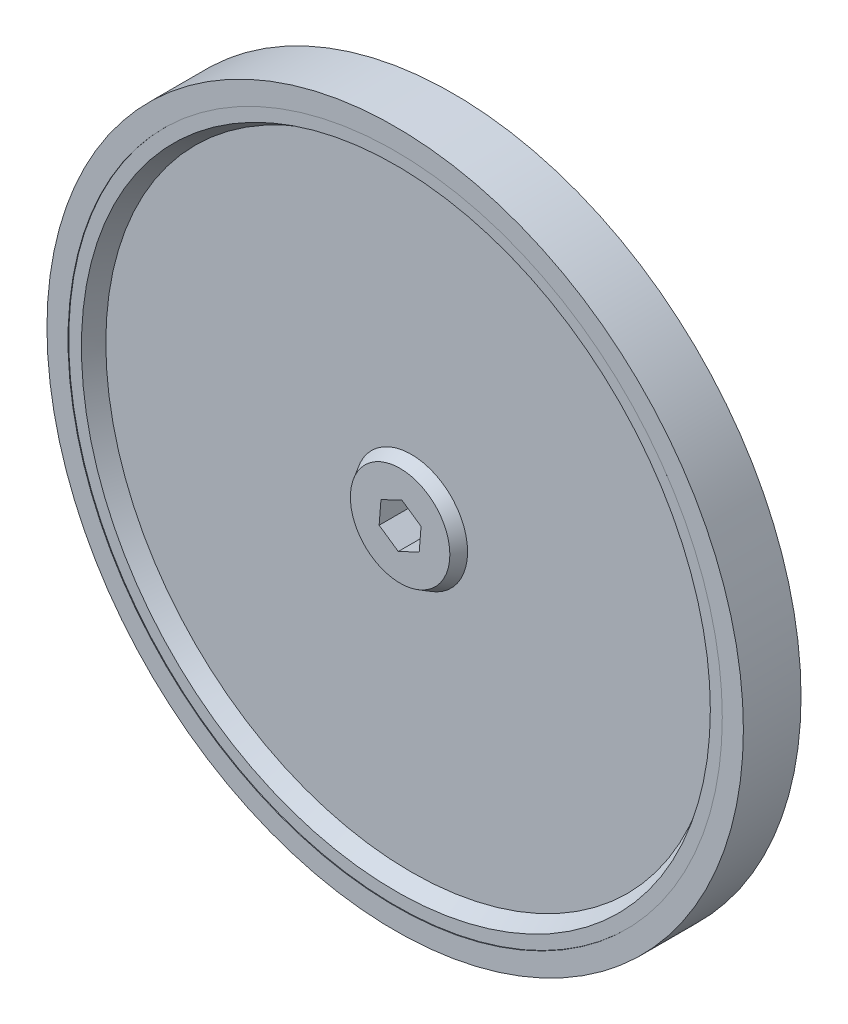
SolidWorks part; units mm, degrees
ref_plane "Front Plane" through (0, 0, 0) normal (0, 0, 1) x (1, 0, 0)
ref_plane "Top Plane" through (0, 0, 0) normal (0, 1, 0) x (1, 0, 0)
ref_plane "Right Plane" through (0, 0, 0) normal (1, 0, 0) x (0, 0, -1)
sketch "Sketch1" plane through (0, 0, 0) normal (0, 0, 1) x (1, 0, 0)
  circle A0 centre (0, 0) radius 123.825
extrude "Boss-Extrude1" add sketch "Sketch1" along normal mid plane 20
sketch "Sketch4" plane through (0, 0, 10) normal (0, 0, 1) x (1, 0, 0)
  circle A0 centre (0, 0) radius 111.825
extrude "Cut-Extrude1" cut sketch "Sketch4" against normal blind 5.5 draft 30
sketch "Sketch5" plane through (0, 0, -10) normal (0, 0, -1) x (-1, 0, 0)
  circle A0 centre (0, 0) radius 111.825
extrude "Cut-Extrude2" cut sketch "Sketch5" against normal blind 5.5 draft 30
sketch "Sketch6" plane through (0, 0, 4.5) normal (0, 0, 1) x (1, 0, 0)
  circle A0 centre (0, 0) radius 20
extrude "Boss-Extrude2" add sketch "Sketch6" along normal blind 4 draft 30 contours A0
sketch "Sketch9" plane through (0, 0, -4.5) normal (0, 0, -1) x (-1, 0, 0)
  circle A0 centre (0, 0) radius 20
extrude "Boss-Extrude3" add sketch "Sketch9" along normal blind 4 draft 30
sketch "Sketch10" plane through (0, 0, -8.5) normal (0, 0, -1) x (-1, 0, 0)
  line L1 (7.4506, -3.5544) -> (6.8035, 4.6752)
  line L2 (6.8035, 4.6752) -> (-0.6471, 8.2296)
  line L3 (-0.6471, 8.2296) -> (-7.4506, 3.5544)
  line L4 (-7.4506, 3.5544) -> (-6.8035, -4.6752)
  line L5 (-6.8035, -4.6752) -> (0.6471, -8.2296)
  line L6 (0.6471, -8.2296) -> (7.4506, -3.5544)
  circle A0 centre (0, 0) radius 7.149 construction
  dimension "D1" = 8.255
extrude "Cut-Extrude4" cut sketch "Sketch10" against normal blind 24
sketch "Sketch11" plane through (0, 0, -10) normal (0, 0, -1) x (-1, 0, 0)
  circle A0 centre (0, 0) radius 116.325
  circle A1 centre (0, 0) radius 123.825
extrude "Boss-Extrude4" add sketch "Sketch11" along normal blind 0.25
sketch "Sketch13" plane through (0, 0, 10) normal (0, 0, 1) x (1, 0, 0)
  circle A0 centre (0, 0) radius 116.325
  circle A1 centre (0, 0) radius 123.825
extrude "Boss-Extrude5" add sketch "Sketch13" along normal blind 0.25
